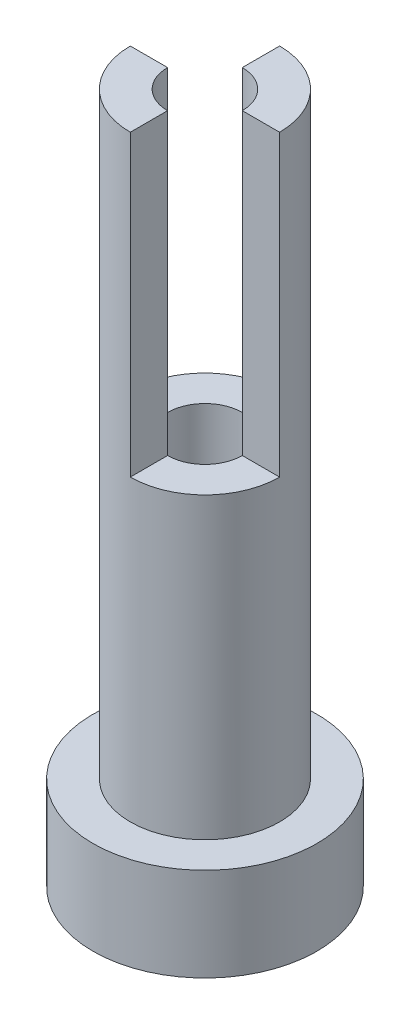
SolidWorks part; units mm, degrees
ref_plane "前视基准面" through (0, 0, 0) normal (0, 0, 1) x (1, 0, 0)
ref_plane "上视基准面" through (0, 0, 0) normal (0, 1, 0) x (1, 0, 0)
ref_plane "右视基准面" through (0, 0, 0) normal (1, 0, 0) x (0, 0, -1)
other "Configuration Table"
sketch "草图1" plane through (0, 0, 0) normal (0, 1, 0) x (1, 0, 0)
  circle A0 centre (0, 0) radius 2
  circle A1 centre (0, 0) radius 1
  dimension "D1" = 4
  dimension "D2" = 2
extrude "凸台-拉伸1" add sketch "草图1" along normal blind 29
sketch "草图2" plane through (0, 0, 0) normal (0, 1, 0) x (1, 0, 0)
  circle A0 centre (0, 0) radius 3
  circle A2 centre (0, 0) radius 2
  circle A3 centre (0, 0) radius 2
  dimension "D2" = 6
  dimension "D1" = 0
extrude "凸台-拉伸2" add sketch "草图2" along normal blind 2.5
sketch "草图3" plane through (0, 0, 0) normal (0, 1, 0) x (1, 0, 0)
  circle A1 centre (0, 0) radius 2
  circle A2 centre (0, 0) radius 2
  circle A3 centre (0, 0) radius 3
  circle A4 centre (0, 0) radius 3
  dimension "D1" = 0
  dimension "D2" = 0
extrude "凸台-拉伸3" add sketch "草图3" against normal blind 2.5 from surface at 29 starting at face at (0, 29, 2)
sketch "草图4" plane through (0, 0, 0) normal (0, 1, 0) x (1, 0, 0)
  circle A0 centre (0, 0) radius 1.6
  dimension "D1" = 3.2
extrude "切除-拉伸1" cut sketch "草图4" along normal blind 1.5
sketch "草图5" plane through (0, 0, 0) normal (0, 1, 0) x (1, 0, 0)
  line L1 (0, -2.3094) -> (2, -1.1547)
  line L2 (2, -1.1547) -> (2, 1.1547)
  line L3 (2, 1.1547) -> (0, 2.3094)
  line L4 (0, 2.3094) -> (-2, 1.1547)
  line L5 (-2, 1.1547) -> (-2, -1.1547)
  line L6 (-2, -1.1547) -> (0, -2.3094)
  circle A0 centre (0, 0) radius 2 construction
  dimension "D1" = 4
extrude "切除-拉伸2" cut sketch "草图5" against normal blind 1.6 from surface at 29 starting at face at (0, 29, 1)
sketch "草图7" plane through (0, 0, 0) normal (0, 1, 0) x (1, 0, 0)
  circle A1 centre (0, 0) radius 3
  circle A2 centre (0, 0) radius 3
  dimension "D1" = 0
extrude "切除-拉伸3" cut sketch "草图7" against normal blind 10.5 from surface at 29 starting at face at (0, 29, 3)
sketch "草图8" plane through (0, 0, 0) normal (0, 1, 0) x (1, 0, 0)
  line L0 (2, 0) -> (-2, 0)
  line L1 (0, -2) -> (0, 2)
  circle A1 centre (0, 0) radius 2
  circle A2 centre (0, 0) radius 2
  dimension "D1" = 0
extrude "切除-拉伸5" cut sketch "草图8" against normal blind 8 from surface at 18.5 contours L1 A2 L0 | L1 A2 L0
